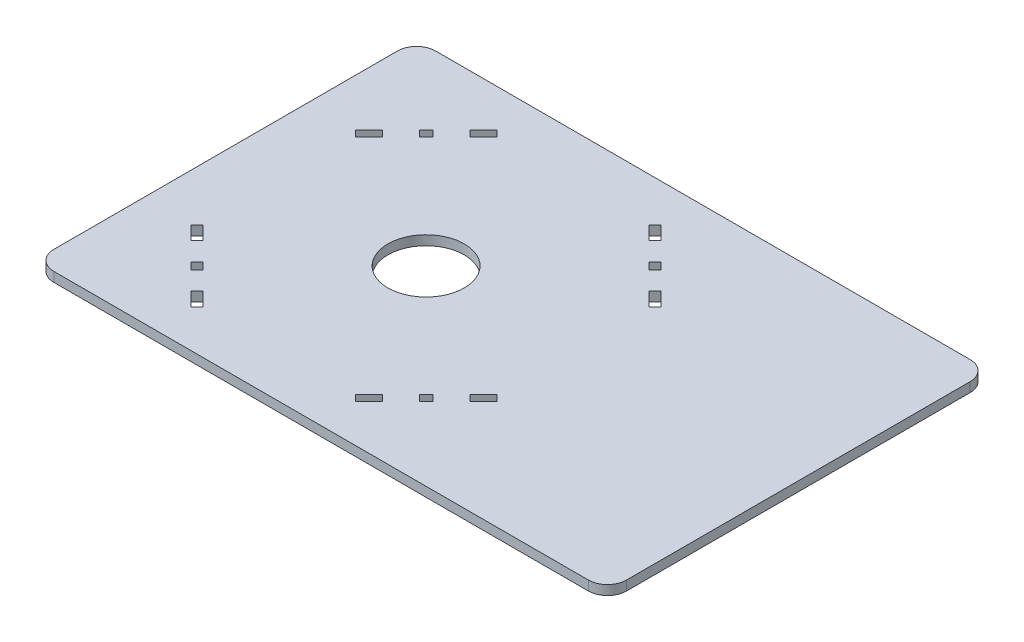
SolidWorks part; units mm, degrees
material "Balsa"
ref_plane "Front Plane" through (0, 0, 0) normal (0, 0, 1) x (1, 0, 0)
ref_plane "Top Plane" through (0, 0, 0) normal (0, 1, 0) x (1, 0, 0)
ref_plane "Right Plane" through (0, 0, 0) normal (1, 0, 0) x (0, 0, -1)
sketch "Sketch1" plane through (0, 0, 0) normal (0, 1, 0) x (1, 0, 0)
  line L0 (-120, 45) -> (-90, 75)
  line L1 (150, -100) -> (-150, -100)
  line L2 (150, -100) -> (150, 100)
  line L3 (150, 100) -> (-150, 100)
  line L4 (-150, -100) -> (-150, 100)
  line L5 (150, -100) -> (-150, 100) construction
  line L6 (150, 100) -> (-150, -100) construction
  line L7 (-90, 75) -> (0, 75)
  line L8 (-120, 45) -> (-120, -45)
  line L9 (-90, -75) -> (0, -75)
  line L10 (30, 45) -> (30, -45)
  line L11 (-120, -45) -> (-90, -75)
  line L12 (0, -75) -> (30, -45)
  line L13 (0, 75) -> (30, 45)
  line L14 (-88.0555, 80.1265) -> (-95.1265, 73.0555)
  line L15 (-88.0555, 80.1265) -> (-84.8735, 76.9445)
  line L16 (-95.1265, 73.0555) -> (-91.9445, 69.8735)
  line L17 (-84.8735, 76.9445) -> (-91.9445, 69.8735)
  line L18 (-88.0555, 80.1265) -> (-91.9445, 69.8735) construction
  line L19 (-95.1265, 73.0555) -> (-84.8735, 76.9445) construction
  line L20 (-121.9445, 39.8735) -> (-114.8735, 46.9445)
  line L21 (-121.9445, 39.8735) -> (-125.1265, 43.0555)
  line L22 (-114.8735, 46.9445) -> (-118.0555, 50.1265)
  line L23 (-125.1265, 43.0555) -> (-118.0555, 50.1265)
  line L24 (-121.9445, 39.8735) -> (-118.0555, 50.1265) construction
  line L25 (-114.8735, 46.9445) -> (-125.1265, 43.0555) construction
  line L26 (-1.9445, 80.1265) -> (5.1265, 73.0555)
  line L27 (-1.9445, 80.1265) -> (-5.1265, 76.9445)
  line L28 (5.1265, 73.0555) -> (1.9445, 69.8735)
  line L29 (-5.1265, 76.9445) -> (1.9445, 69.8735)
  line L30 (-1.9445, 80.1265) -> (1.9445, 69.8735) construction
  line L31 (5.1265, 73.0555) -> (-5.1265, 76.9445) construction
  line L32 (35.1265, 43.0555) -> (28.0555, 50.1265)
  line L33 (35.1265, 43.0555) -> (31.9445, 39.8735)
  line L34 (28.0555, 50.1265) -> (24.8735, 46.9445)
  line L35 (31.9445, 39.8735) -> (24.8735, 46.9445)
  line L36 (35.1265, 43.0555) -> (24.8735, 46.9445) construction
  line L37 (28.0555, 50.1265) -> (31.9445, 39.8735) construction
  line L38 (-1.9445, -80.1265) -> (5.1265, -73.0555)
  line L39 (-1.9445, -80.1265) -> (-5.1265, -76.9445)
  line L40 (5.1265, -73.0555) -> (1.9445, -69.8735)
  line L41 (-5.1265, -76.9445) -> (1.9445, -69.8735)
  line L42 (-1.9445, -80.1265) -> (1.9445, -69.8735) construction
  line L43 (5.1265, -73.0555) -> (-5.1265, -76.9445) construction
  line L44 (35.1265, -43.0555) -> (28.0555, -50.1265)
  line L45 (35.1265, -43.0555) -> (31.9445, -39.8735)
  line L46 (28.0555, -50.1265) -> (24.8735, -46.9445)
  line L47 (31.9445, -39.8735) -> (24.8735, -46.9445)
  line L48 (35.1265, -43.0555) -> (24.8735, -46.9445) construction
  line L49 (28.0555, -50.1265) -> (31.9445, -39.8735) construction
  line L50 (-125.1265, -43.0555) -> (-118.0555, -50.1265)
  line L51 (-125.1265, -43.0555) -> (-121.9445, -39.8735)
  line L52 (-118.0555, -50.1265) -> (-114.8735, -46.9445)
  line L53 (-121.9445, -39.8735) -> (-114.8735, -46.9445)
  line L54 (-125.1265, -43.0555) -> (-114.8735, -46.9445) construction
  line L55 (-118.0555, -50.1265) -> (-121.9445, -39.8735) construction
  line L56 (-88.0555, -80.1265) -> (-95.1265, -73.0555)
  line L57 (-88.0555, -80.1265) -> (-84.8735, -76.9445)
  line L58 (-95.1265, -73.0555) -> (-91.9445, -69.8735)
  line L59 (-84.8735, -76.9445) -> (-91.9445, -69.8735)
  line L60 (-88.0555, -80.1265) -> (-91.9445, -69.8735) construction
  line L61 (-95.1265, -73.0555) -> (-84.8735, -76.9445) construction
  line L62 (15, 60) -> (-105, -60) construction
  line L63 (-105, 60) -> (15, -60) construction
  line L64 (15.1768, 56.6412) -> (11.6412, 60.1768)
  line L65 (15.1768, 56.6412) -> (18.3588, 59.8232)
  line L66 (11.6412, 60.1768) -> (14.8232, 63.3588)
  line L67 (18.3588, 59.8232) -> (14.8232, 63.3588)
  line L68 (15.1768, 56.6412) -> (14.8232, 63.3588) construction
  line L69 (11.6412, 60.1768) -> (18.3588, 59.8232) construction
  line L70 (15.1768, -56.6412) -> (11.6412, -60.1768)
  line L71 (15.1768, -56.6412) -> (18.3588, -59.8232)
  line L72 (11.6412, -60.1768) -> (14.8232, -63.3588)
  line L73 (18.3588, -59.8232) -> (14.8232, -63.3588)
  line L74 (15.1768, -56.6412) -> (14.8232, -63.3588) construction
  line L75 (11.6412, -60.1768) -> (18.3588, -59.8232) construction
  line L76 (-101.6412, -60.1768) -> (-105.1768, -56.6412)
  line L77 (-101.6412, -60.1768) -> (-104.8232, -63.3588)
  line L78 (-105.1768, -56.6412) -> (-108.3588, -59.8232)
  line L79 (-104.8232, -63.3588) -> (-108.3588, -59.8232)
  line L80 (-101.6412, -60.1768) -> (-108.3588, -59.8232) construction
  line L81 (-105.1768, -56.6412) -> (-104.8232, -63.3588) construction
  line L82 (-105.1768, 56.6412) -> (-101.6412, 60.1768)
  line L83 (-105.1768, 56.6412) -> (-108.3588, 59.8232)
  line L84 (-101.6412, 60.1768) -> (-104.8232, 63.3588)
  line L85 (-108.3588, 59.8232) -> (-104.8232, 63.3588)
  line L86 (-105.1768, 56.6412) -> (-104.8232, 63.3588) construction
  line L87 (-101.6412, 60.1768) -> (-108.3588, 59.8232) construction
  circle A0 centre (-45, 0) radius 20
  point P0 (0, 0)
  point P6 (-120, 75)
  point P7 (30, -75)
  point P8 (-120, -75)
  point P9 (30, 75)
  point P54 (-45, 0)
  dimension "D27" = 40
  dimension "D1" = 200
  dimension "D2" = 300
  dimension "D3" = 25
  dimension "D4" = 30
  dimension "D5" = 25
  dimension "D6" = 150
  dimension "D7" = 10
  dimension "D8" = 4.5
  dimension "D9" = 10
  dimension "D10" = 4.5
  dimension "D11" = 4.5
  dimension "D12" = 10
  dimension "D17" = 4.5
  dimension "D18" = 10
  dimension "D19" = 4.5
  dimension "D20" = 10
  dimension "D21" = 10
  dimension "D22" = 4.5
  dimension "D23" = 4.5
  dimension "D24" = 10
  dimension "D25" = 4.5
  dimension "D26" = 10
  dimension "D28" = 5
  dimension "D29" = 4.5
  dimension "D30" = 4.5
  dimension "D31" = 5
  dimension "D32" = 4.5
  dimension "D33" = 5
  dimension "D34" = 5
  dimension "D35" = 4.5
extrude "Boss-Extrude2" add sketch "Sketch1" along normal blind 5 contours L59 L9 L41 L40 L12 L46 L47 L10 L35 L34 L13 L28 L29 L7 L17 L16 L0 L22 L20 L8 L53 L52 L11 L58 | L4 L1 L2 L3 L59 L57 L56 L58 L11 L52 L50 L51 L53 L8 L20 L21 L23 L22 L0 L16 L14 L15 L17 L7 L29 L27 L26 L28 L13 L34 L32 L33 L35 L10 L47 L45 L44 L46 L12 L40 L38 L39 L41 L9
fillet "Fillet1" radius 10 4 edges at (-150, 2.5, -100) (150, 2.5, -100) (150, 2.5, 100) (-150, 2.5, 100)
